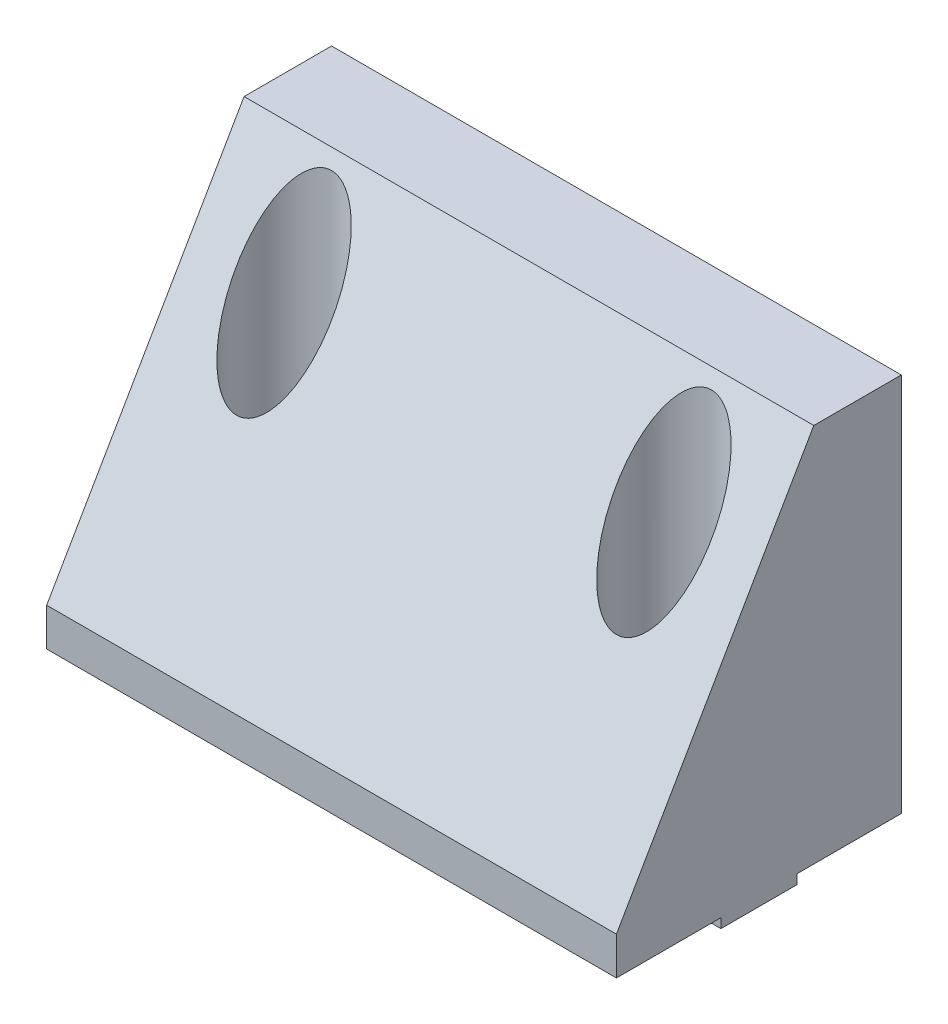
SolidWorks part; units mm, degrees
material "3D printed plastic"
ref_plane "Front Plane" through (0, 0, 0) normal (0, 0, 1) x (1, 0, 0)
ref_plane "Top Plane" through (0, 0, 0) normal (0, 1, 0) x (1, 0, 0)
ref_plane "Right Plane" through (0, 0, 0) normal (1, 0, 0) x (0, 0, -1)
sketch "Sketch1" plane through (0, 0, 0) normal (1, 0, 0) x (0, 0, -1)
  line L0 (-15, 0) -> (15, 0)
  line L1 (15, 0) -> (15, 40)
  line L2 (15, 40) -> (5.7846, 40)
  line L3 (5.7846, 40) -> (-15, 4)
  line L4 (-15, 4) -> (-15, 0)
  dimension "D1" = 30
  dimension "D2" = 30
  dimension "D3" = 4
  dimension "D4" = 40
extrude "Boss-Extrude1" add sketch "Sketch1" along normal mid plane 60
sketch "Sketch2" plane through (0, 0, 0) normal (0, -1, 0) x (1, 0, 0)
  line L0 (20, 0) -> (-20, 0) construction
  circle A0 centre (-20, 0) radius 2.25
  circle A1 centre (20, 0) radius 2.25
  dimension "D1" = 4.5
  dimension "D2" = 40
extrude "Cut-Extrude1" cut sketch "Sketch2" against normal through all
sketch "Sketch3" plane through (0, 0, 0) normal (0, -1, 0) x (1, 0, 0)
  circle A0 centre (-20, 0) radius 5
  circle A1 centre (20, 0) radius 5
  dimension "D1" = 10
extrude "Cut-Extrude2" cut sketch "Sketch3" against normal through all from offset 13 offset against normal yes
sketch "Sketch4" plane through (0, 0, 0) normal (0, -1, 0) x (1, 0, 0)
  line L0 (-30, 15) -> (-30, -15) construction
  line L1 (-30, 4) -> (30, 4)
  line L2 (-30, 4) -> (-30, -4)
  line L3 (-30, -4) -> (30, -4)
  line L4 (30, 4) -> (30, -4)
  line L5 (30, 15) -> (30, -15) construction
  line L6 (20, 0) -> (30, 0) construction
  line L7 (-20, 0) -> (-30, 0) construction
  circle A0 centre (-20, 0) radius 2.25
  circle A1 centre (20, 0) radius 2.25
  circle A2 centre (20, 0) radius 2.25 construction
  circle A3 centre (-20, 0) radius 2.25 construction
  dimension "D1" = 8
extrude "Boss-Extrude2" add sketch "Sketch4" along normal blind 1
